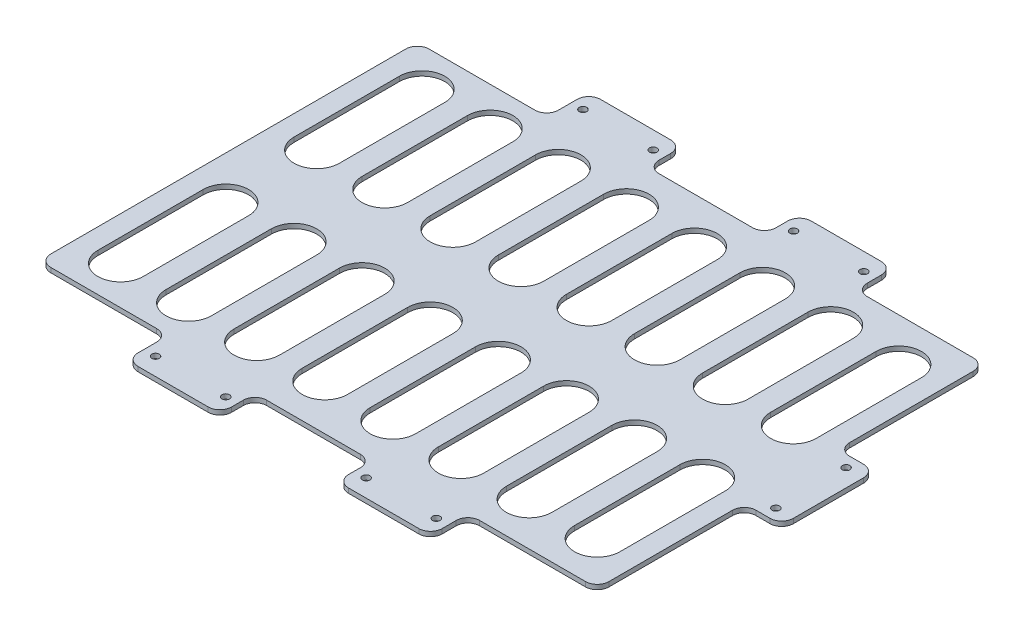
SolidWorks part; units mm, degrees
material "Thornel Mat VMA"
ref_plane "前视基准面" through (0, 0, 0) normal (0, 0, 1) x (1, 0, 0)
ref_plane "上视基准面" through (0, 0, 0) normal (0, 1, 0) x (1, 0, 0)
ref_plane "右视基准面" through (0, 0, 0) normal (1, 0, 0) x (0, 0, -1)
sketch "草图1" plane through (0, 0, 0) normal (0, 1, 0) x (1, 0, 0)
  line L0 (0, 83.825) -> (0, -83.825) construction
  line L1 (-121.25, -83.825) -> (121.25, -83.825)
  line L2 (-121.25, -83.825) -> (-121.25, 83.825)
  line L3 (-121.25, 83.825) -> (121.25, 83.825)
  line L4 (121.25, -83.825) -> (121.25, 83.825)
  line L5 (-121.25, -83.825) -> (121.25, 83.825) construction
  line L6 (-121.25, 83.825) -> (121.25, -83.825) construction
  line L11 (-65, 91.325) -> (-60, 91.325) construction
  line L12 (-65, 83.825) -> (-25, 83.825)
  line L13 (-65, 83.825) -> (-65, 98.825)
  line L14 (-65, 98.825) -> (-25, 98.825)
  line L15 (-25, 83.825) -> (-25, 98.825)
  line L16 (-60, 91.325) -> (-30, 91.325) construction
  line L17 (-30, 91.325) -> (-25, 91.325) construction
  line L18 (65, 98.825) -> (25, 98.825)
  line L19 (25, 83.825) -> (25, 98.825)
  line L20 (65, 83.825) -> (25, 83.825)
  line L21 (65, 83.825) -> (65, 98.825)
  line L22 (-121.25, 0) -> (121.25, 0) construction
  line L23 (-65, -98.825) -> (-25, -98.825)
  line L24 (-25, -83.825) -> (-25, -98.825)
  line L25 (-65, -83.825) -> (-25, -83.825)
  line L26 (-65, -83.825) -> (-65, -98.825)
  line L27 (65, -83.825) -> (65, -98.825)
  line L28 (65, -83.825) -> (25, -83.825)
  line L29 (25, -83.825) -> (25, -98.825)
  line L30 (65, -98.825) -> (25, -98.825)
  line L31 (128.75, 20) -> (128.75, 15) construction
  line L32 (121.25, 20) -> (136.25, 20)
  line L33 (121.25, 20) -> (121.25, -20)
  line L34 (121.25, -20) -> (136.25, -20)
  line L35 (136.25, 20) -> (136.25, -20)
  line L36 (128.75, 15) -> (128.75, -15) construction
  line L37 (128.75, -15) -> (128.75, -20) construction
  circle A0 centre (-60, 91.325) radius 1.6
  circle A1 centre (-30, 91.325) radius 1.6
  circle A2 centre (30, 91.325) radius 1.6
  circle A3 centre (60, 91.325) radius 1.6
  circle A4 centre (30, -91.325) radius 1.6
  circle A5 centre (60, -91.325) radius 1.6
  circle A6 centre (-60, -91.325) radius 1.6
  circle A7 centre (-30, -91.325) radius 1.6
  circle A8 centre (128.75, 15) radius 1.6
  circle A9 centre (128.75, -15) radius 1.6
  point P0 (0, 0)
  dimension "D7" = 3.2
  dimension "D1" = 167.65
  dimension "D2" = 242.5
  dimension "D3" = 40
  dimension "D4" = 40
  dimension "D5" = 15
  dimension "D6" = 5
  dimension "D8" = 130
  dimension "D9" = 15
extrude "凸台-拉伸1" add sketch "草图1" along normal blind 2
sketch "草图4" plane through (0, 2, 0) normal (0, 1, 0) x (1, 0, 0)
  line L0 (-121.25, 0) -> (121.25, 0) construction
  line L1 (-121.25, -83.825) -> (-121.25, 83.825) construction
  line L2 (121.25, 20) -> (121.25, -20) construction
  line L3 (-101.85, 64.425) -> (-101.85, 19.4) construction
  line L4 (-92.15, 64.425) -> (-92.15, 19.4)
  line L5 (-111.55, 64.425) -> (-111.55, 19.4)
  line L6 (-111.55, 41.9125) -> (-121.25, 41.9125) construction
  line L7 (-101.85, 74.125) -> (-101.85, 83.825) construction
  line L8 (-121.25, 83.825) -> (-65, 83.825) construction
  line L9 (-101.85, 9.7) -> (-101.85, 0) construction
  line L10 (-72.75, 64.425) -> (-72.75, 19.4) construction
  line L11 (-63.05, 64.425) -> (-63.05, 19.4)
  line L12 (-82.45, 64.425) -> (-82.45, 19.4)
  line L13 (-43.65, 64.425) -> (-43.65, 19.4) construction
  line L14 (-33.95, 64.425) -> (-33.95, 19.4)
  line L15 (-53.35, 64.425) -> (-53.35, 19.4)
  line L16 (-14.55, 64.425) -> (-14.55, 19.4) construction
  line L17 (-4.85, 64.425) -> (-4.85, 19.4)
  line L18 (-24.25, 64.425) -> (-24.25, 19.4)
  line L19 (14.55, 64.425) -> (14.55, 19.4) construction
  line L20 (24.25, 64.425) -> (24.25, 19.4)
  line L21 (4.85, 64.425) -> (4.85, 19.4)
  line L22 (43.65, 64.425) -> (43.65, 19.4) construction
  line L23 (53.35, 64.425) -> (53.35, 19.4)
  line L24 (33.95, 64.425) -> (33.95, 19.4)
  line L25 (72.75, 64.425) -> (72.75, 19.4) construction
  line L26 (82.45, 64.425) -> (82.45, 19.4)
  line L27 (63.05, 64.425) -> (63.05, 19.4)
  line L28 (101.85, 64.425) -> (101.85, 19.4) construction
  line L29 (111.55, 64.425) -> (111.55, 19.4)
  line L30 (92.15, 64.425) -> (92.15, 19.4)
  line L31 (101.85, -64.425) -> (101.85, -19.4) construction
  line L32 (111.55, -64.425) -> (111.55, -19.4)
  line L33 (92.15, -64.425) -> (92.15, -19.4)
  line L34 (72.75, -64.425) -> (72.75, -19.4) construction
  line L35 (82.45, -64.425) -> (82.45, -19.4)
  line L36 (63.05, -64.425) -> (63.05, -19.4)
  line L37 (43.65, -64.425) -> (43.65, -19.4) construction
  line L38 (53.35, -64.425) -> (53.35, -19.4)
  line L39 (33.95, -64.425) -> (33.95, -19.4)
  line L40 (14.55, -64.425) -> (14.55, -19.4) construction
  line L41 (24.25, -64.425) -> (24.25, -19.4)
  line L42 (4.85, -64.425) -> (4.85, -19.4)
  line L43 (-14.55, -64.425) -> (-14.55, -19.4) construction
  line L44 (-4.85, -64.425) -> (-4.85, -19.4)
  line L45 (-24.25, -64.425) -> (-24.25, -19.4)
  line L46 (-43.65, -64.425) -> (-43.65, -19.4) construction
  line L47 (-33.95, -64.425) -> (-33.95, -19.4)
  line L48 (-53.35, -64.425) -> (-53.35, -19.4)
  line L49 (-72.75, -64.425) -> (-72.75, -19.4) construction
  line L50 (-63.05, -64.425) -> (-63.05, -19.4)
  line L51 (-82.45, -64.425) -> (-82.45, -19.4)
  line L52 (-101.85, -64.425) -> (-101.85, -19.4) construction
  line L53 (-92.15, -64.425) -> (-92.15, -19.4)
  line L54 (-111.55, -64.425) -> (-111.55, -19.4)
  arc A0 (-92.15, 64.425) -> (-111.55, 64.425) centre (-101.85, 64.425) ccw
  arc A1 (-111.55, 19.4) -> (-92.15, 19.4) centre (-101.85, 19.4) ccw
  arc A2 (-63.05, 64.425) -> (-82.45, 64.425) centre (-72.75, 64.425) ccw
  arc A3 (-82.45, 19.4) -> (-63.05, 19.4) centre (-72.75, 19.4) ccw
  arc A4 (-33.95, 64.425) -> (-53.35, 64.425) centre (-43.65, 64.425) ccw
  arc A5 (-53.35, 19.4) -> (-33.95, 19.4) centre (-43.65, 19.4) ccw
  arc A6 (-4.85, 64.425) -> (-24.25, 64.425) centre (-14.55, 64.425) ccw
  arc A7 (-24.25, 19.4) -> (-4.85, 19.4) centre (-14.55, 19.4) ccw
  arc A8 (24.25, 64.425) -> (4.85, 64.425) centre (14.55, 64.425) ccw
  arc A9 (4.85, 19.4) -> (24.25, 19.4) centre (14.55, 19.4) ccw
  arc A10 (53.35, 64.425) -> (33.95, 64.425) centre (43.65, 64.425) ccw
  arc A11 (33.95, 19.4) -> (53.35, 19.4) centre (43.65, 19.4) ccw
  arc A12 (82.45, 64.425) -> (63.05, 64.425) centre (72.75, 64.425) ccw
  arc A13 (63.05, 19.4) -> (82.45, 19.4) centre (72.75, 19.4) ccw
  arc A14 (111.55, 64.425) -> (92.15, 64.425) centre (101.85, 64.425) ccw
  arc A15 (92.15, 19.4) -> (111.55, 19.4) centre (101.85, 19.4) ccw
  arc A16 (111.55, -64.425) -> (92.15, -64.425) centre (101.85, -64.425) cw
  arc A17 (92.15, -19.4) -> (111.55, -19.4) centre (101.85, -19.4) cw
  arc A18 (82.45, -64.425) -> (63.05, -64.425) centre (72.75, -64.425) cw
  arc A19 (63.05, -19.4) -> (82.45, -19.4) centre (72.75, -19.4) cw
  arc A20 (53.35, -64.425) -> (33.95, -64.425) centre (43.65, -64.425) cw
  arc A21 (33.95, -19.4) -> (53.35, -19.4) centre (43.65, -19.4) cw
  arc A22 (24.25, -64.425) -> (4.85, -64.425) centre (14.55, -64.425) cw
  arc A23 (4.85, -19.4) -> (24.25, -19.4) centre (14.55, -19.4) cw
  arc A24 (-4.85, -64.425) -> (-24.25, -64.425) centre (-14.55, -64.425) cw
  arc A25 (-24.25, -19.4) -> (-4.85, -19.4) centre (-14.55, -19.4) cw
  arc A26 (-33.95, -64.425) -> (-53.35, -64.425) centre (-43.65, -64.425) cw
  arc A27 (-53.35, -19.4) -> (-33.95, -19.4) centre (-43.65, -19.4) cw
  arc A28 (-63.05, -64.425) -> (-82.45, -64.425) centre (-72.75, -64.425) cw
  arc A29 (-82.45, -19.4) -> (-63.05, -19.4) centre (-72.75, -19.4) cw
  arc A30 (-92.15, -64.425) -> (-111.55, -64.425) centre (-101.85, -64.425) cw
  arc A31 (-111.55, -19.4) -> (-92.15, -19.4) centre (-101.85, -19.4) cw
  point P9 (-101.85, 41.9125)
  point P25 (-72.75, 41.9125)
  point P32 (-43.65, 41.9125)
  point P39 (-14.55, 41.9125)
  point P46 (14.55, 41.9125)
  point P53 (43.65, 41.9125)
  point P60 (72.75, 41.9125)
  point P67 (101.85, 41.9125)
  point P75 (101.85, -41.9125)
  point P82 (72.75, -41.9125)
  point P89 (43.65, -41.9125)
  point P96 (14.55, -41.9125)
  point P103 (-14.55, -41.9125)
  point P110 (-43.65, -41.9125)
  point P117 (-72.75, -41.9125)
  point P124 (-101.85, -41.9125)
  dimension "D1" = 9.7
  dimension "D2" = 19.4
  dimension "D4" = 9.7
  dimension "D3" = 8
extrude "切除-拉伸3" cut sketch "草图4" against normal through all
sketch "草图5" plane through (0, 2, 0) normal (0, 1, 0) x (1, 0, 0)
  line L0 (-65, 83.825) -> (-65, 80.825)
  line L1 (-65, 80.825) -> (-120.25, 80.825)
  line L2 (-120.25, 80.825) -> (-120.25, -80.825)
  line L3 (-120.25, -80.825) -> (-65, -80.825)
  line L4 (-65, -80.825) -> (-65, -83.825)
  line L5 (65, -83.825) -> (65, -82.825)
  line L6 (65, -82.825) -> (120.25, -82.825)
  line L7 (121.25, -20) -> (120.25, -20)
  line L8 (120.25, -20) -> (120.25, -82.825)
  line L9 (121.25, 20) -> (120.25, 20)
  line L10 (120.25, 20) -> (120.25, 82.825)
  line L11 (120.25, 82.825) -> (65, 82.825)
  line L12 (65, 82.825) -> (65, 83.825)
  line L14 (-120.25, 0) -> (-121.25, 0) construction
  line L15 (-121.25, -83.825) -> (-121.25, 83.825) construction
  line L16 (-65, 83.825) -> (-121.25, 83.825)
  line L17 (-121.25, 83.825) -> (-121.25, -83.825)
  line L18 (-121.25, -83.825) -> (-65, -83.825)
  line L19 (65, -83.825) -> (121.25, -83.825)
  line L20 (121.25, -83.825) -> (121.25, -20)
  line L21 (121.25, 20) -> (121.25, 83.825)
  line L22 (121.25, 83.825) -> (65, 83.825)
  line L23 (65, 83.825) -> (65, 98.825) construction
  point P18 (-120.25, -1.187)
  point P22 (0, 0)
  dimension "D1" = 3
  dimension "D2" = 1
extrude "切除-拉伸4" cut sketch "草图5" against normal through all
fillet "圆角2" radius 5 24 edges at (-120.25, 1, -80.825) (-120.25, 1, 80.825) (-65, 1, 98.825) (-25, 1, 98.825) (-25, 1, 83.825) (25, 1, 83.825) (25, 1, 98.825) (65, 1, 98.825) (65, 1, 82.825) (120.25, 1, 82.825) (120.25, 1, 20) (136.25, 1, 20) (136.25, 1, -20) (120.25, 1, -20) (120.25, 1, -82.825) (65, 1, -82.825) (65, 1, -98.825) (25, 1, -98.825) (25, 1, -83.825) (-25, 1, -83.825) (-25, 1, -98.825) (-65, 1, -98.825) (-65, 1, -80.825) (-65, 1, 80.825)
